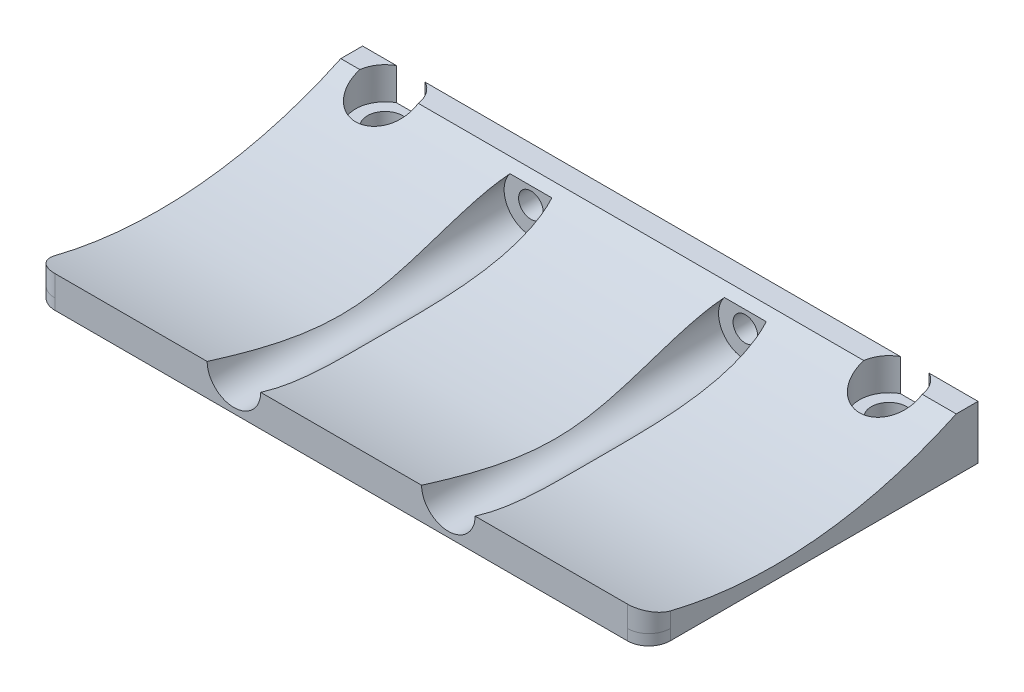
SolidWorks part; units mm, degrees
ref_plane "Front Plane" through (0, 0, 0) normal (0, 0, 1) x (1, 0, 0)
ref_plane "Top Plane" through (0, 0, 0) normal (0, 1, 0) x (1, 0, 0)
ref_plane "Right Plane" through (0, 0, 0) normal (1, 0, 0) x (0, 0, -1)
sketch "Sketch1" plane through (0, 0, 0) normal (0, 1, 0) x (1, 0, 0)
  line L0 (4.5, 28.3) -> (4.5, 4.7) construction
  line L1 (0, 0) -> (57.4, 0)
  line L2 (0, 0) -> (0, 33)
  line L3 (0, 33) -> (57.4, 33)
  line L4 (57.4, 0) -> (57.4, 33)
  circle A0 centre (4.5, 28.3) radius 1.65
  circle A1 centre (51.5, 28.3) radius 1.65
  circle A2 centre (4.5, 4.7) radius 1.65
  circle A3 centre (51.5, 4.7) radius 1.65
  point P13 (0, 16.5)
  point P14 (4.5, 16.5)
  point P15 (0, 0)
  dimension "D3" = 3.3
  dimension "D4" = 47
  dimension "D5" = 23.6
  dimension "D6" = 4.5
  dimension "D1" = 57.4
  dimension "D2" = 33
extrude "Boss-Extrude1" add sketch "Sketch1" along normal blind 1
sketch "Sketch2" plane through (0, 1, 0) normal (0, 1, 0) x (1, 0, 0)
  line L0 (57.4, 0) -> (57.4, 33) construction
  line L1 (0, 33) -> (57.4, 33)
  line L2 (0, 33) -> (0, 30.7)
  line L3 (0, 30.7) -> (57.4, 30.7)
  line L4 (57.4, 33) -> (57.4, 30.7)
  dimension "D1" = 2.3
extrude "Cut-Extrude1" cut sketch "Sketch2" against normal up to next
sketch "Sketch3" plane through (57.4, 0, 0) normal (1, 0, 0) x (0, 0, -1)
  line L0 (30.7, 1) -> (30.7, 5)
  line L1 (30.7, 5) -> (28.7, 5)
  line L2 (28.7, 5) -> (20.7, 1)
  line L3 (0, 1) -> (30.7, 1) construction
  line L4 (20.7, 1) -> (30.7, 1)
  dimension "D1" = 4
  dimension "D2" = 10
  dimension "D3" = 2
extrude "Boss-Extrude2" add sketch "Sketch3" against normal up to surface (57.4 mm away) up to face at (0, 0.5, -15.35)
fillet "Fillet1" radius 2 2 edges at (0, 0.5, 0) (57.4, 0.5, 0)
sketch "Sketch10" plane through (0, 0, 0) normal (1, 0, 0) x (0, 0, -1)
  line L0 (2, 1) -> (0, 1) construction
  line L1 (0, 1) -> (0, 0) construction
  line L2 (0, 0) -> (2, 0) construction
  line L3 (20.7, 1) -> (2, 1) construction
  line L4 (2, 0) -> (30.7, 0) construction
  line L5 (30.7, 0) -> (30.7, 5) construction
  line L6 (30.7, 5) -> (28.7, 5) construction
  line L7 (28.7, 5) -> (20.7, 1) construction
  line L8 (2, 1) -> (0, 1)
  line L9 (0, 1) -> (0, 0)
  line L10 (0, 0) -> (2, 0)
  line L11 (20.7, 1) -> (2, 1)
  line L12 (2, 0) -> (30.7, 0)
  line L13 (30.7, 0) -> (30.7, 5)
  line L14 (30.7, 5) -> (28.7, 5)
  line L15 (28.7, 5) -> (20.7, 1)
  line L16 (0, 1) -> (0, 2.9741)
  line L17 (28.7, 5) -> (28.6687, 5)
  circle A0 centre (11.703, 41.2238) radius 40
  dimension "D1" = 80
extrude "Boss-Extrude3" add sketch "Sketch10" along direction (-1, 0, 0) on the side of the normal up to surface (57.4 mm away) contours A0 L16 L8 L11 L15 L17
sketch "Sketch4" plane through (0, 0, 0) normal (0, -1, 0) x (-1, 0, 0)
  circle A0 centre (-4.5, 28.3) radius 1.65
  circle A1 centre (-51.5, 28.3) radius 1.65
  dimension "D1" = 3.3
extrude "Cut-Extrude2" cut sketch "Sketch4" against normal blind 2
sketch "Sketch5" plane through (0, 2, 0) normal (0, -1, 0) x (-1, 0, 0)
  circle A0 centre (-4.5, 28.3) radius 2.75
  circle A1 centre (-51.5, 28.3) radius 2.75
  dimension "D1" = 5.5
extrude "Cut-Extrude3" cut sketch "Sketch5" against normal up to next
sketch "Sketch6" plane through (0, 0, -30.7) normal (0, 0, -1) x (-1, 0, 0)
  circle A0 centre (-38.7, 3) radius 1.15
  circle A1 centre (-18.7, 3) radius 1.15
  dimension "D1" = 2.3
extrude "Cut-Extrude4" cut sketch "Sketch6" against normal blind 3
sketch "Sketch9" plane through (0, 0, -27.7) normal (0, 0, -1) x (-1, 0, 0)
  circle A0 centre (-38.7, 3) radius 2.5
  circle A1 centre (-18.7, 3) radius 2.5
  dimension "D1" = 5
extrude "Cut-Extrude5" cut sketch "Sketch9" against normal through all
fillet "Fillet2" radius 2 2 edges at (0, 1.9871, 0) (57.4, 1.9871, 0)
